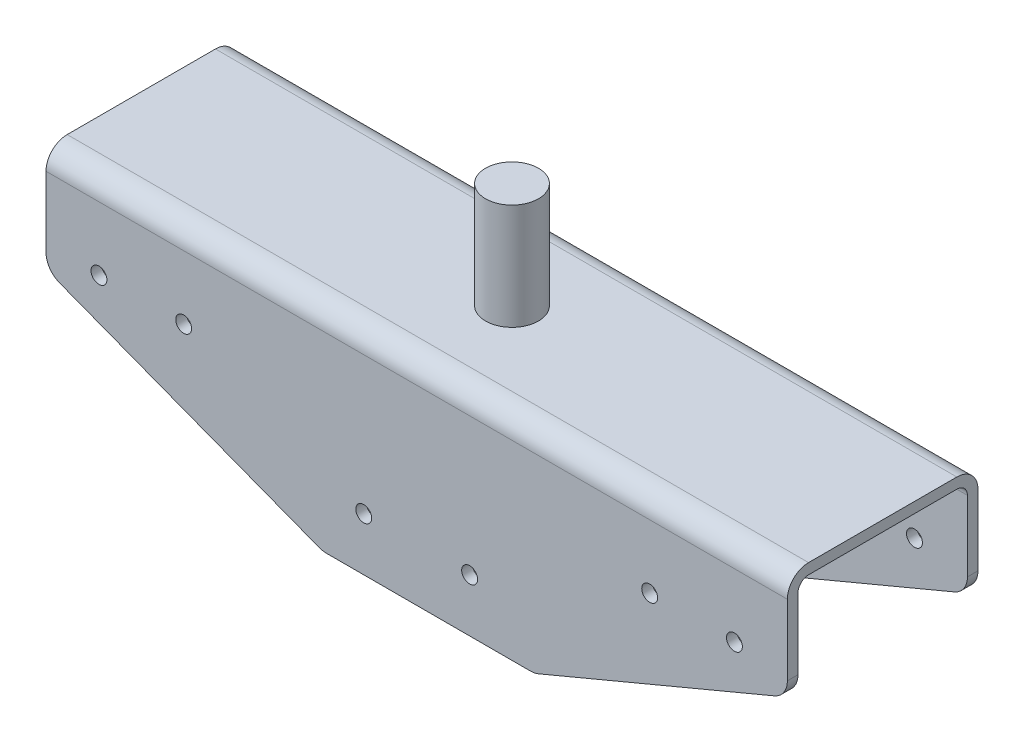
SolidWorks part; units mm, degrees
ref_plane "Front Plane" through (0, 0, 0) normal (0, 0, 1) x (1, 0, 0)
ref_plane "Top Plane" through (0, 0, 0) normal (0, 1, 0) x (1, 0, 0)
ref_plane "Right Plane" through (0, 0, 0) normal (1, 0, 0) x (0, 0, -1)
sketch "Sketch1" plane through (0, 0, 0) normal (0, 0, 1) x (1, 0, 0)
  line L1 (-8.4984, -10) -> (10.73, -10)
  line L2 (-35, 1.3761) -> (-35, 10)
  line L3 (-35, 10) -> (35, 10)
  line L4 (35, 1.3305) -> (35, 10)
  line L5 (-20.0386, -5.7253) -> (35, 10) construction
  line L6 (-35, 10) -> (20.8093, -5.9455) construction
  line L8 (-33.7148, -0.4918) -> (-9.2132, -9.8679)
  line L9 (-8.868, -10) -> (11.132, -10)
  line L10 (11.5028, -9.8446) -> (33.7729, -0.5141)
  arc A0 (35, 1.3305) -> (33.7729, -0.5141) centre (33, 1.3305) cw
  arc A1 (11.5028, -9.8446) -> (10.73, -10) centre (10.73, -8) cw
  arc A2 (-8.4984, -10) -> (-9.2132, -9.8679) centre (-8.4984, -8) cw
  arc A3 (-33.7148, -0.4918) -> (-35, 1.3761) centre (-33, 1.3761) cw
  point P0 (0, 0)
  point P11 (35, 0)
  point P21 (-35, 0)
  dimension "D6" = 2
  dimension "D1" = 70
  dimension "D2" = 10
  dimension "D3" = 20
  dimension "D4" = 10
  dimension "D5" = 20
extrude "Boss-Extrude1" add sketch "Sketch1" along normal mid plane 18 contours A3 L8 A2 L1 A1 L10 A0 L4 L3 L2
fillet "Fillet1" radius 2 2 edges at (0, 10, -9) (0, 10, 9)
sketch "Sketch2" plane through (0, 0, 0) normal (1, 0, 0) x (0, 0, -1)
  line L9 (-8, 8) -> (-8, -14.2343)
  line L10 (-8, -14.2343) -> (8, -14.2343)
  line L11 (8, 8) -> (8, 1.3305)
  line L12 (-7, 9) -> (7, 9)
  line L13 (8, 8) -> (8, 1.3305)
  line L14 (-7, 9) -> (7, 9)
  line L15 (8, -14.2343) -> (8, 1.3305)
  arc A2 (-7, 9) -> (-8, 8) centre (-7, 8) ccw
  arc A3 (-7, 9) -> (-8, 8) centre (-7, 8) ccw
  arc A8 (8, 8) -> (7, 9) centre (7, 8) ccw
  arc A9 (8, 8) -> (7, 9) centre (7, 8) ccw
  dimension "D1" = 1
  dimension "D2" = 1
extrude "Cut-Extrude1" cut sketch "Sketch2" against normal through all both and the other way through all
sketch "Sketch3" plane through (0, 10, 0) normal (0, 1, 0) x (1, 0, 0)
  circle A0 centre (0, 0) radius 2.5
  dimension "D1" = 5
extrude "Boss-Extrude2" add sketch "Sketch3" along normal blind 10
sketch "Sketch4" plane through (0, 0, 0) normal (0, 0, 1) x (1, 0, 0)
  line L0 (0, 0) -> (0, -18.6662) construction
  line L1 (-35, 10) -> (35, 10) construction
  line L2 (-8.4984, -10) -> (10.73, -10) construction
  line L3 (-35, 1.3761) -> (-35, 8) construction
  circle A0 centre (-30, 2) radius 0.75
  circle A1 centre (-22, 2) radius 0.75
  circle A4 centre (-5, -5) radius 0.75
  circle A5 centre (5, -5) radius 0.75
  circle A6 centre (22, 2) radius 0.75
  circle A7 centre (30, 2) radius 0.75
  dimension "D1" = 1.5
  dimension "D2" = 1.5
  dimension "D5" = 1.5
  dimension "D3" = 8
  dimension "D4" = 8
  dimension "D6" = 5
  dimension "D7" = 5
  dimension "D8" = 5
extrude "Cut-Extrude2" cut sketch "Sketch4" against normal through all both and the other way through all
sketch "Sketch5" plane through (0, 9, 0) normal (0, -1, 0) x (1, 0, 0)
  line L0 (-35, -7) -> (35, -7) construction
  line L1 (0, 5) -> (1, 5)
  line L2 (0, 5) -> (0, -5)
  line L3 (0, -5) -> (1, -5)
  line L4 (1, 5) -> (1, -5)
  line L5 (-35, 7) -> (35, 7) construction
  dimension "D1" = 2
  dimension "D2" = 2
  dimension "D3" = 1
extrude "Boss-Extrude3" add sketch "Sketch5" along normal blind 10
equation "\"1。5\"=2"
